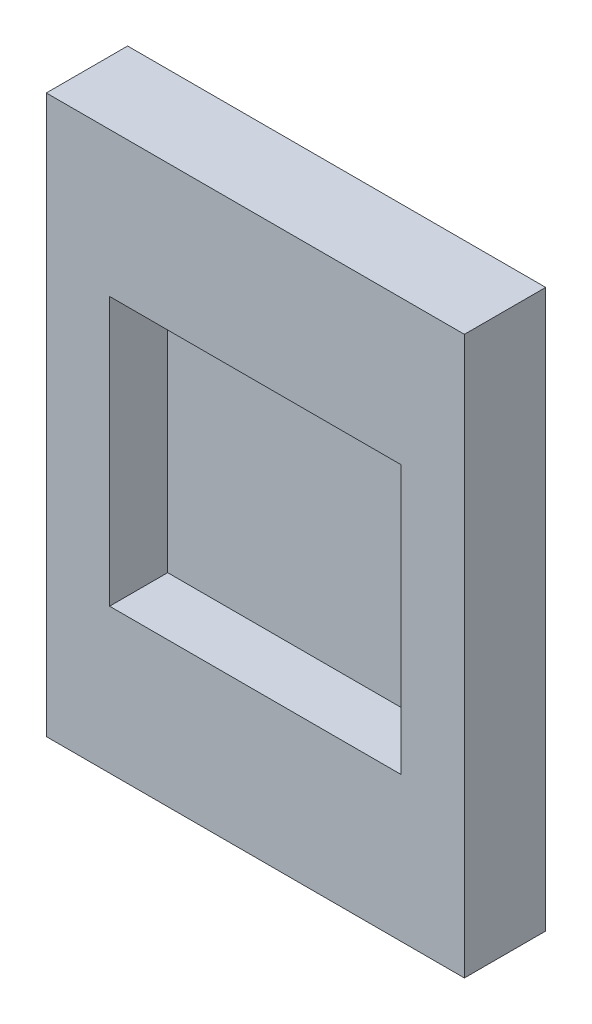
SolidWorks part; units mm, degrees
ref_plane "정면" through (0, 0, 0) normal (0, 0, 1) x (1, 0, 0)
ref_plane "윗면" through (0, 0, 0) normal (0, 1, 0) x (1, 0, 0)
ref_plane "우측면" through (0, 0, 0) normal (1, 0, 0) x (0, 0, -1)
sketch "스케치1" plane through (0, 0, 0) normal (0, 0, 1) x (1, 0, 0)
  line L1 (-9, -12) -> (9, -12)
  line L2 (-9, -12) -> (-9, 12)
  line L3 (-9, 12) -> (9, 12)
  line L4 (9, -12) -> (9, 12)
  line L5 (-9, -12) -> (9, 12) construction
  line L6 (-9, 12) -> (9, -12) construction
  point P0 (0, 0)
  dimension "D1" = 18
  dimension "D2" = 24
extrude "보스-돌출1" add sketch "스케치1" along normal blind 3.5
sketch "스케치2" plane through (0, 0, 3.5) normal (0, 0, 1) x (1, 0, 0)
  line L1 (-6.275, -5.775) -> (6.275, -5.775)
  line L2 (-6.275, -5.775) -> (-6.275, 5.775)
  line L3 (-6.275, 5.775) -> (6.275, 5.775)
  line L4 (6.275, -5.775) -> (6.275, 5.775)
  line L5 (-6.275, -5.775) -> (6.275, 5.775) construction
  line L6 (-6.275, 5.775) -> (6.275, -5.775) construction
  point P1 (0, 0)
  dimension "D1" = 12.55
  dimension "D2" = 11.55
extrude "컷-돌출1" cut sketch "스케치2" against normal blind 2.5
